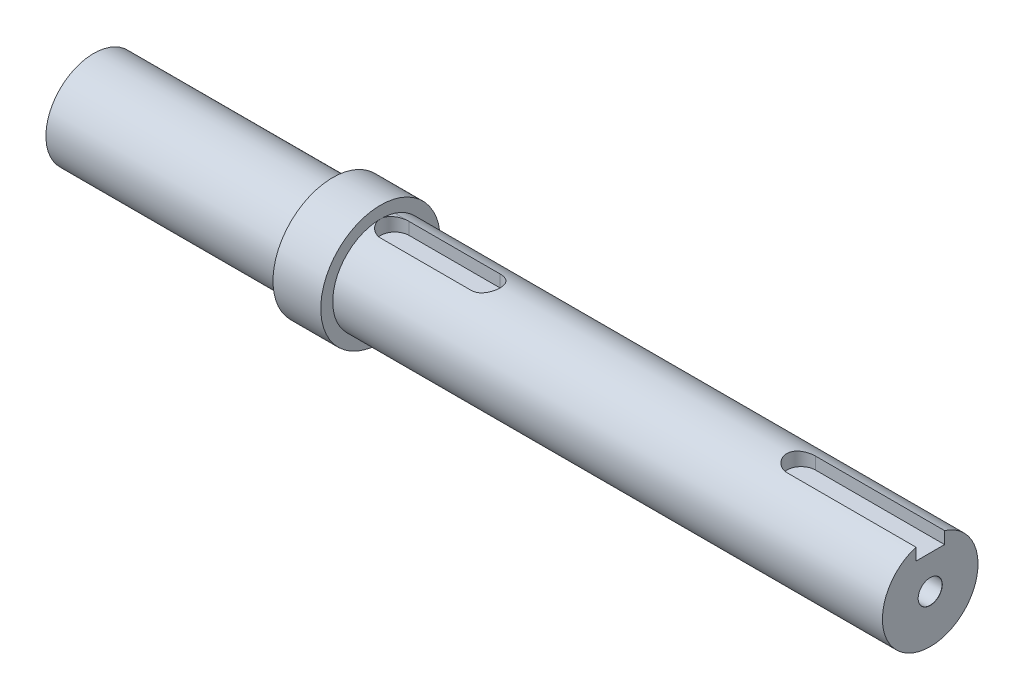
SolidWorks part; units mm, degrees
ref_plane "Front Plane" through (0, 0, 0) normal (0, 0, 1) x (1, 0, 0)
ref_plane "Top Plane" through (0, 0, 0) normal (0, 1, 0) x (1, 0, 0)
ref_plane "Right Plane" through (0, 0, 0) normal (1, 0, 0) x (0, 0, -1)
sketch "Sketch1" plane through (0, 0, 0) normal (0, 1, 0) x (1, 0, 0)
  line L0 (0, 0) -> (0, 10)
  line L1 (0, 10) -> (50, 10)
  line L2 (50, 10) -> (50, 12.5)
  line L3 (50, 12.5) -> (60, 12.5)
  line L4 (60, 12.5) -> (60, 10)
  line L5 (60, 10) -> (175, 10)
  line L6 (175, 10) -> (175, 0)
  line L7 (175, 0) -> (0, 0)
  dimension "D1" = 10
  dimension "D2" = 12.5
  dimension "D3" = 50
  dimension "D4" = 115
  dimension "D5" = 10
  dimension "D6" = 10
revolve "Revolve1" add sketch "Sketch1" angle 360 about L7
hole_wizard "Ø5.0mm Dowel Hole1" positions "3DSketch2" profile "Sketch3" hole size "Ø5.0" standard "ISO"
sketch3d "3DSketch2"
  line L0 (0, 0, 0) -> (0, 0, 14.1375) construction
  line L1 (0, 0, 14.1375) -> (0, 4.6927, 14.1375) construction
  line L3 (0, 0, 0) -> (0, 6.6157, 0) construction
  point P0 (0, 0, 0)
  point P3 (0, 0, 0)
  dimension "D1" = 0
sketch "Sketch3" plane through (0, 0, 0) normal (0, 1, 0) x (0, 0, 1)
  line L0 (0, 0) -> (0, 11.5022)
  line L1 (0, 11.5022) -> (2.5, 10)
  line L2 (2.5, 10) -> (2.5, 0.025)
  line L3 (2.5, 0.025) -> (2.525, 0)
  line L5 (2.525, 0) -> (0, 0)
  line L6 (-2.5, 0.025) -> (-2.525, 0) construction
  line L10 (0, 11.5022) -> (-2.5, 10) construction
  line L11 (0, -6.35) -> (0, 107.95) construction
  dimension "Hole Dia." = 5
  dimension "Hole Depth" = 10
  dimension "Near C'Sink Dia." = 5.05
  dimension "Near C'Sink Angle" = 90
  dimension "Drill Angle" = 118
sketch "Sketch8" plane through (175, 0, 0) normal (1, 0, 0) x (0, 0, -1)
  line L0 (0, 0) -> (15.7935, 0) construction
  line L1 (0, 0) -> (0, 11.1042) construction
hole_wizard "Ø5.0mm Dowel Hole2" positions "3DSketch5" profile "Sketch9" hole size "Ø5.0" standard "ISO"
sketch3d "3DSketch5"
  point P0 (0, 0, 0)
  point P3 (175, 0, 0)
  dimension "D1" = 0
sketch "Sketch9" plane through (175, 0, 0) normal (0, 1, 0) x (0, 0, -1)
  line L0 (0, 0) -> (0, 11.5022)
  line L1 (0, 11.5022) -> (2.5, 10)
  line L2 (2.5, 10) -> (2.5, 0.025)
  line L3 (2.5, 0.025) -> (2.525, 0)
  line L5 (2.525, 0) -> (0, 0)
  line L6 (-2.5, 0.025) -> (-2.525, 0) construction
  line L10 (0, 11.5022) -> (-2.5, 10) construction
  line L11 (0, -6.35) -> (0, 107.95) construction
  dimension "Hole Dia." = 5
  dimension "Hole Depth" = 10
  dimension "Near C'Sink Dia." = 5.05
  dimension "Near C'Sink Angle" = 90
  dimension "Drill Angle" = 118
ref_plane "Plane1" through (0, 10, 0) normal (0, 1, 0) x (1, 0, 0)
sketch "Sketch10" plane through (0, 10, 0) normal (0, 1, 0) x (1, 0, 0)
  line L0 (63, 0) -> (82, 0) construction
  line L1 (63, 3) -> (82, 3)
  line L2 (63, -3) -> (82, -3)
  line L3 (60, -12.5) -> (60, 12.5) construction
  line L4 (175, 0) -> (148, 0) construction
  line L5 (175, 0) -> (175, 15.7935) construction
  line L6 (175, -3) -> (148, -3)
  line L7 (175, 3) -> (148, 3)
  arc A0 (63, 3) -> (63, -3) centre (63, 0) ccw
  arc A1 (82, -3) -> (82, 3) centre (82, 0) ccw
  arc A2 (175, -3) -> (175, 3) centre (175, 0) ccw
  arc A3 (148, 3) -> (148, -3) centre (148, 0) ccw
  point P3 (72.5, 0)
  point P8 (85, 0)
  point P9 (60, 0)
  point P16 (161.5, 0)
  point P22 (145, 0)
  dimension "D2" = 25
  dimension "D1" = 6
  dimension "D3" = 0
  dimension "D4" = 6
  dimension "D5" = 30
extrude "Cut-Extrude1" cut sketch "Sketch10" against normal blind 3
